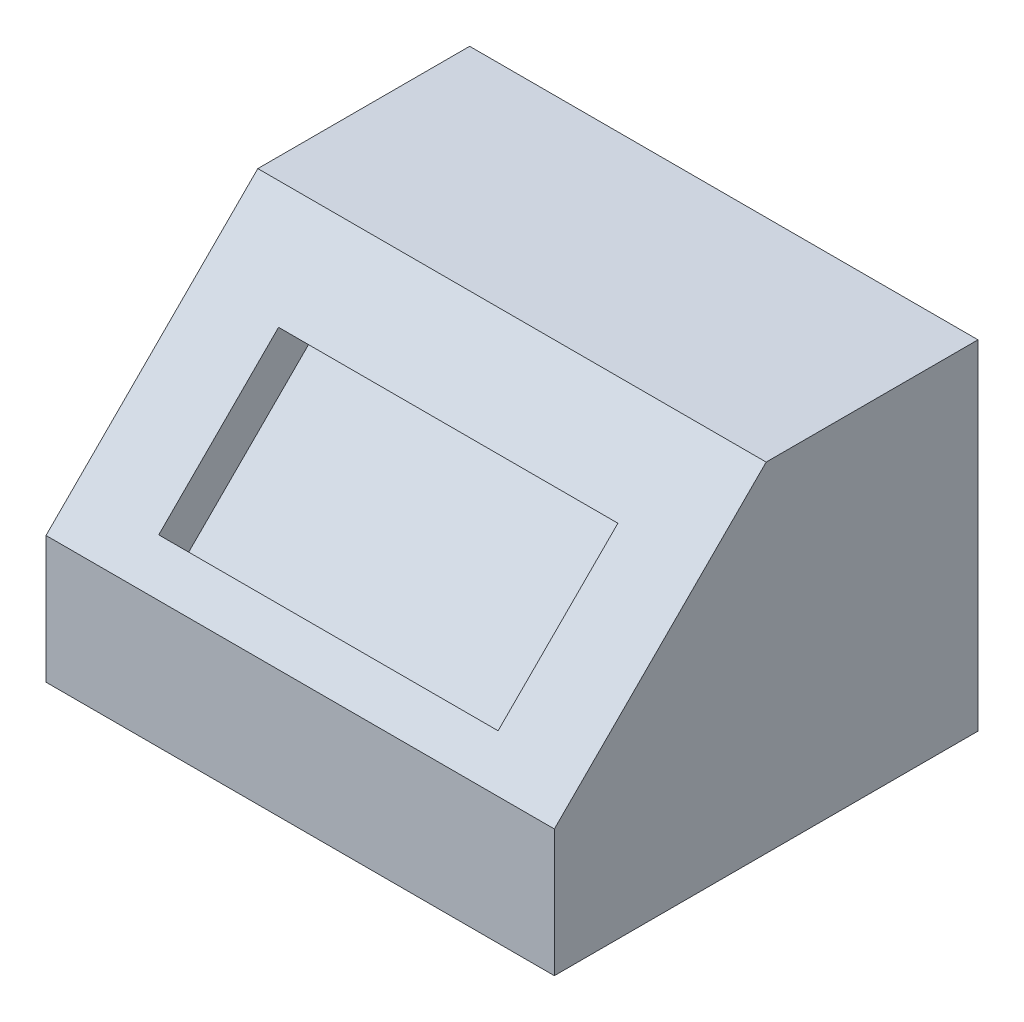
SolidWorks part; units mm, degrees
ref_plane "Front Plane" through (0, 0, 0) normal (0, 0, 1) x (1, 0, 0)
ref_plane "Top Plane" through (0, 0, 0) normal (0, 1, 0) x (1, 0, 0)
ref_plane "Right Plane" through (0, 0, 0) normal (1, 0, 0) x (0, 0, -1)
sketch "Sketch1" plane through (0, 0, 0) normal (0, 0, 1) x (1, 0, 0)
  line L1 (28.7175, 30.8115) -> (-123.6825, 30.8115)
  line L2 (28.7175, 30.8115) -> (28.7175, -70.7885)
  line L3 (28.7175, -70.7885) -> (-123.6825, -70.7885)
  line L4 (-123.6825, 30.8115) -> (-123.6825, -70.7885)
extrude "Boss-Extrude1" add sketch "Sketch1" against normal blind 127
sketch "Sketch2" plane through (0, 0, 0) normal (1, 0, 0) x (0, 0, -1)
  line L0 (0, 30.8115) -> (0, -32.6885)
  line L1 (0, -70.7885) -> (0, 30.8115) construction
  line L2 (0, -32.6885) -> (63.5, 30.8115)
  line L3 (127, 30.8115) -> (0, 30.8115) construction
  line L4 (63.5, 30.8115) -> (0, 30.8115)
extrude "Cut-Extrude1" cut sketch "Sketch2" along normal blind 134.62 contours L4 L0 L2
sketch "Sketch3" plane through (0, 0, 0) normal (1, 0, 0) x (0, 0, -1)
  line L0 (0, -32.6885) -> (0, 30.8115)
  line L1 (0, 30.8115) -> (63.5, 30.8115)
  line L2 (63.5, 30.8115) -> (0, -32.6885)
extrude "Cut-Extrude2" cut sketch "Sketch3" against normal blind 134.62
ref_plane "Plane1" through (0, 28.1057, -28.1057) normal (0, -0.7071, 0.7071) x (1, 0, 0)
sketch "Sketch5" plane through (0, 28.1057, -28.1057) normal (0, -0.7071, 0.7071) x (1, 0, 0)
  line L1 (-123.6825, -23.1143) -> (28.7175, -23.1143) construction
  line L3 (-98.415, -23.1143) -> (3.3175, -23.1143)
  line L4 (-98.415, -23.1143) -> (-98.415, -35.8143)
  line L5 (-98.415, -35.8143) -> (3.3175, -35.8143)
  line L6 (3.3175, -23.1143) -> (3.3175, -35.8143)
  point P0 (-98.415, -23.1143)
extrude "Cut-Extrude4" cut sketch "Sketch5" along normal blind 50.8
